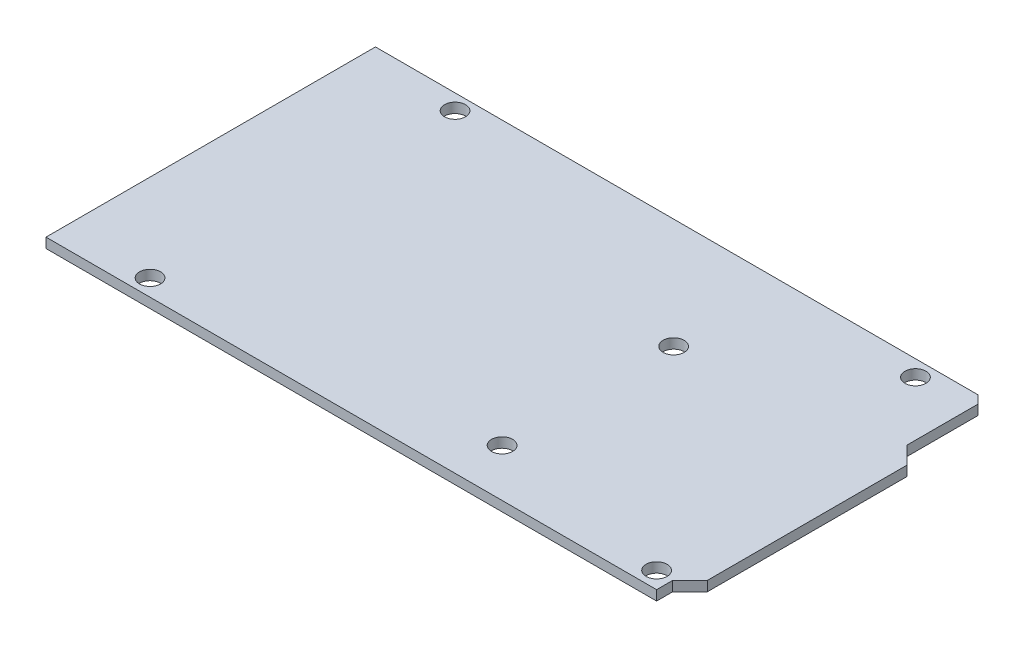
SolidWorks part; units mm, degrees
ref_plane "Front Plane" through (0, 0, 0) normal (0, 0, 1) x (1, 0, 0)
ref_plane "Top Plane" through (0, 0, 0) normal (0, 1, 0) x (1, 0, 0)
ref_plane "Right Plane" through (0, 0, 0) normal (1, 0, 0) x (0, 0, -1)
sketch "Sketch1" plane through (0, 0, 0) normal (0, 1, 0) x (1, 0, 0)
  line L0 (98.6, 0) -> (98.6, 2.6)
  line L1 (0, 0) -> (98.6, 0)
  line L2 (0, 0) -> (0, 53.2)
  line L3 (0, 53.2) -> (97.3, 53.2)
  line L4 (101.4, 5.4) -> (101.4, 37.6)
  line L5 (98.6, 2.6) -> (101.4, 5.4)
  line L6 (101.4, 37.6) -> (98.6, 40.4)
  line L7 (98.6, 40.4) -> (98.6, 51.9)
  line L8 (98.6, 51.9) -> (97.3, 53.2)
  circle A0 centre (95.9, 2.7) radius 1.7
  circle A1 centre (89.8, 50.6) radius 1.7
  circle A2 centre (65.95, 35.4) radius 1.7
  circle A3 centre (65.95, 7.7) radius 1.7
  circle A4 centre (15.35, 50.7) radius 1.7
  circle A5 centre (14.1, 2.7) radius 1.7
  dimension "D10" = 3.4
  dimension "D11" = 1
  dimension "D15" = 6
  dimension "D1" = 101.4
  dimension "D2" = 53.2
  dimension "D3" = 135
  dimension "D4" = 135
  dimension "D5" = 135
  dimension "D6" = 1.3
  dimension "D7" = 11.5
  dimension "D8" = 2.8
  dimension "D9" = 2.6
  dimension "D12" = 1
  dimension "D13" = 0.9
  dimension "D14" = 7.1
  dimension "D16" = 16.1
  dimension "D17" = 33.75
  dimension "D18" = 0.8
  dimension "D19" = 1
  dimension "D20" = 13.65
  dimension "D21" = 12.4
extrude "Boss-Extrude1" add sketch "Sketch1" along normal blind 1.6
